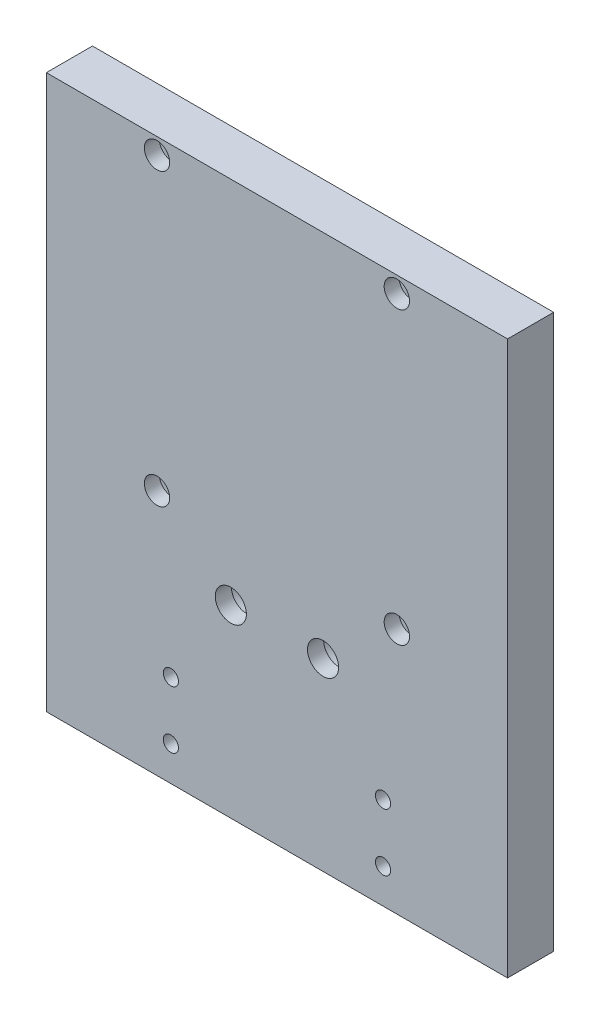
SolidWorks part; units mm, degrees
material "6061 合金"
ref_plane "前视基准面" through (0, 0, 0) normal (0, 0, 1) x (1, 0, 0)
ref_plane "上视基准面" through (0, 0, 0) normal (0, 1, 0) x (1, 0, 0)
ref_plane "右视基准面" through (0, 0, 0) normal (1, 0, 0) x (0, 0, -1)
other "Configuration Table"
sketch "Sketch1" plane through (0, 0, 0) normal (0, 0, 1) x (1, 0, 0)
  line L1 (-120, -170) -> (120, -170)
  line L2 (-120, -170) -> (-120, 70)
  line L3 (-120, 70) -> (120, 70)
  line L4 (120, -170) -> (120, 70)
extrude "Boss-Extrude1" add sketch "Sketch1" along normal blind 20
sketch "Sketch2" plane through (0, 0, 0) normal (0, 0, 1) x (1, 0, 0)
  circle A0 centre (-52, -63) radius 3.3
  circle A1 centre (-52, 63) radius 3.3
  circle A2 centre (52, -63) radius 3.3
  circle A3 centre (52, 63) radius 3.3
extrude "Cut-Extrude1" cut sketch "Sketch2" against normal through all and the other way through all
ref_plane "Plane1" through (0, 0, 20) normal (0, 0, 1) x (1, 0, 0)
sketch "Sketch3" plane through (0, 0, 20) normal (0, 0, 1) x (1, 0, 0)
  circle A0 centre (-52, -63) radius 5.5
  circle A1 centre (-52, 63) radius 5.5
  circle A2 centre (52, -63) radius 5.5
  circle A3 centre (52, 63) radius 5.5
extrude "Cut-Extrude3" cut sketch "Sketch3" against normal blind 6.5
sketch "Sketch4" plane through (0, 0, 0) normal (0, 0, 1) x (1, 0, 0)
  circle A0 centre (-20, -90) radius 6.75
  circle A1 centre (20, -90) radius 6.75
extrude "Cut-Extrude4" cut sketch "Sketch4" against normal through all and the other way through all
sketch "Sketch5" plane through (0, 0, 0) normal (0, 0, 1) x (1, 0, 0)
  circle A0 centre (-20, -90) radius 10
  circle A1 centre (20, -90) radius 10
extrude "Cut-Extrude6" cut sketch "Sketch5" along normal blind 13
sketch "Sketch6" plane through (0, 0, 0) normal (0, 0, 1) x (1, 0, 0)
  circle A0 centre (-46, -130) radius 3.3
  circle A1 centre (-46, -155) radius 3.3
  circle A2 centre (46, -130) radius 3.3
  circle A3 centre (46, -155) radius 3.3
extrude "Cut-Extrude7" cut sketch "Sketch6" against normal through all and the other way through all
sketch "Sketch7" plane through (0, 0, 0) normal (0, 0, 1) x (1, 0, 0)
  circle A0 centre (-46, -130) radius 5.5
  circle A1 centre (-46, -155) radius 5.5
  circle A2 centre (46, -130) radius 5.5
  circle A3 centre (46, -155) radius 5.5
extrude "Cut-Extrude9" cut sketch "Sketch7" along normal blind 6.5
sketch "Sketch8" plane through (0, 0, 0) normal (0, 0, 1) x (1, 0, 0)
  line L1 (-130, -180) -> (-100, -180)
  line L2 (-130, -180) -> (-130, 80)
  line L3 (-130, 80) -> (-100, 80)
  line L4 (-100, -180) -> (-100, 80)
  line L6 (100, -180) -> (130, -180)
  line L7 (100, -180) -> (100, 80)
  line L8 (100, 80) -> (130, 80)
  line L9 (130, -180) -> (130, 80)
extrude "Cut-Extrude10" cut sketch "Sketch8" against normal through all and the other way through all
